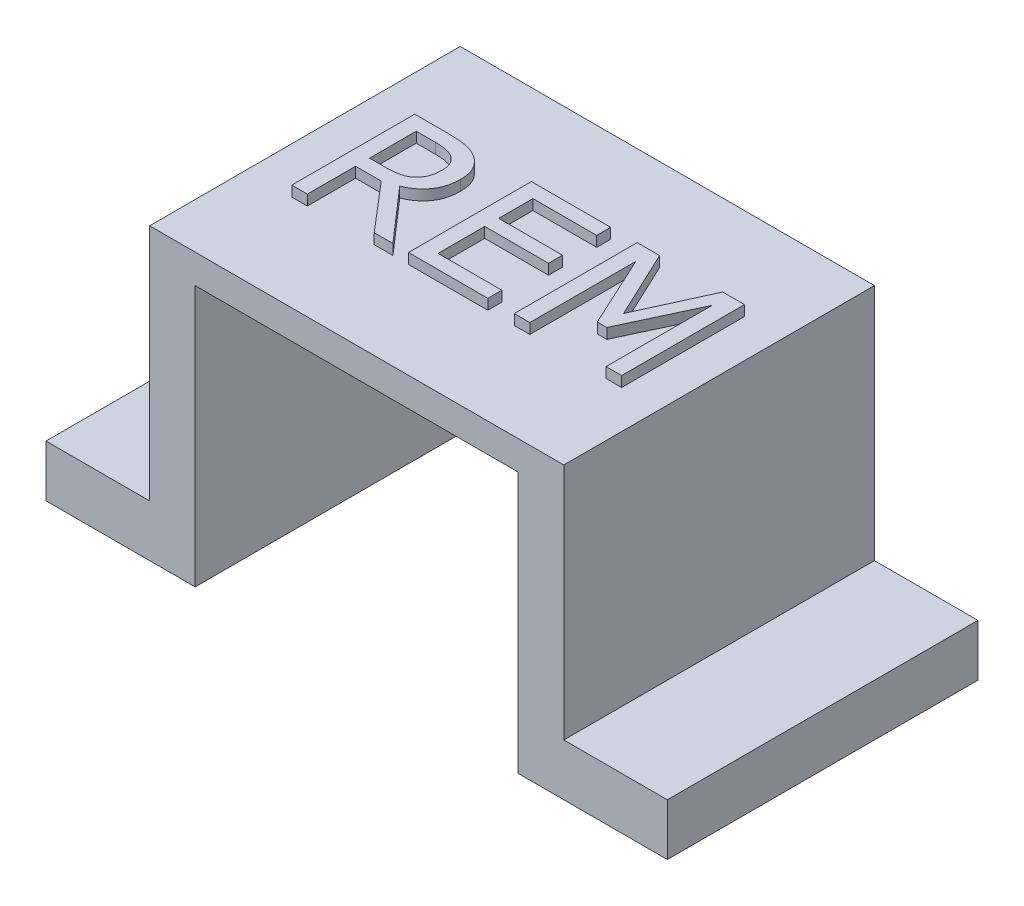
SolidWorks part; units mm, degrees
ref_plane "Alzado" through (0, 0, 0) normal (0, 0, 1) x (1, 0, 0)
ref_plane "Planta" through (0, 0, 0) normal (0, 1, 0) x (1, 0, 0)
ref_plane "Vista lateral" through (0, 0, 0) normal (1, 0, 0) x (0, 0, -1)
sketch "Croquis1" plane through (0, 0, 0) normal (0, 0, 1) x (1, 0, 0)
  line L1 (-10, 14) -> (10, 14)
  line L2 (-10, 14) -> (-10, 0)
  line L3 (-10, 0) -> (10, 0)
  line L4 (10, 14) -> (10, 0)
  point P4 (0, 0)
  dimension "D1" = 14
  dimension "D2" = 20
extrude "Saliente-Extruir1" add sketch "Croquis1" along normal blind 15
sketch "Croquis2" plane through (0, 0, 15) normal (0, 0, 1) x (1, 0, 0)
  line L1 (-7.8, 12.6) -> (7.8, 12.6)
  line L2 (-7.8, 12.6) -> (-7.8, 0)
  line L3 (-7.8, 0) -> (7.8, 0)
  line L4 (7.8, 12.6) -> (7.8, 0)
  line L5 (-7.8, 12.6) -> (7.8, 0) construction
  line L6 (-7.8, 0) -> (7.8, 12.6) construction
  point P0 (0, 0)
  point P2 (0, 6.3)
  dimension "D2" = 12.6
  dimension "D3" = 15.6
extrude "Cortar-Extruir1" cut sketch "Croquis2" against normal through all
sketch "Croquis3" plane through (10, 0, 0) normal (1, 0, 0) x (0, 0, -1)
  line L0 (-15, 0) -> (-15, 14) construction
  line L1 (0, 0) -> (-15, 0)
  line L2 (0, 0) -> (0, 2.5)
  line L3 (0, 2.5) -> (-15, 2.5)
  line L4 (-15, 0) -> (-15, 2.5)
  dimension "D1" = 2.5
extrude "Saliente-Extruir2" add sketch "Croquis3" along normal blind 5
sketch "Croquis4" plane through (-10, 0, 0) normal (-1, 0, 0) x (0, 0, 1)
  line L0 (15, 14) -> (15, 0) construction
  line L1 (0, 0) -> (15, 0)
  line L2 (0, 0) -> (0, 2.5)
  line L3 (0, 2.5) -> (15, 2.5)
  line L4 (15, 0) -> (15, 2.5)
  dimension "D1" = 2.5
extrude "Saliente-Extruir3" add sketch "Croquis4" along normal blind 5
sketch "Croquis5" plane through (0, 14, 0) normal (0, 1, 0) x (1, 0, 0)
  text T0 "REM" font "Verdana" height in points 22
extrude "Saliente-Extruir4" add sketch "Croquis5" along normal blind 0.5
